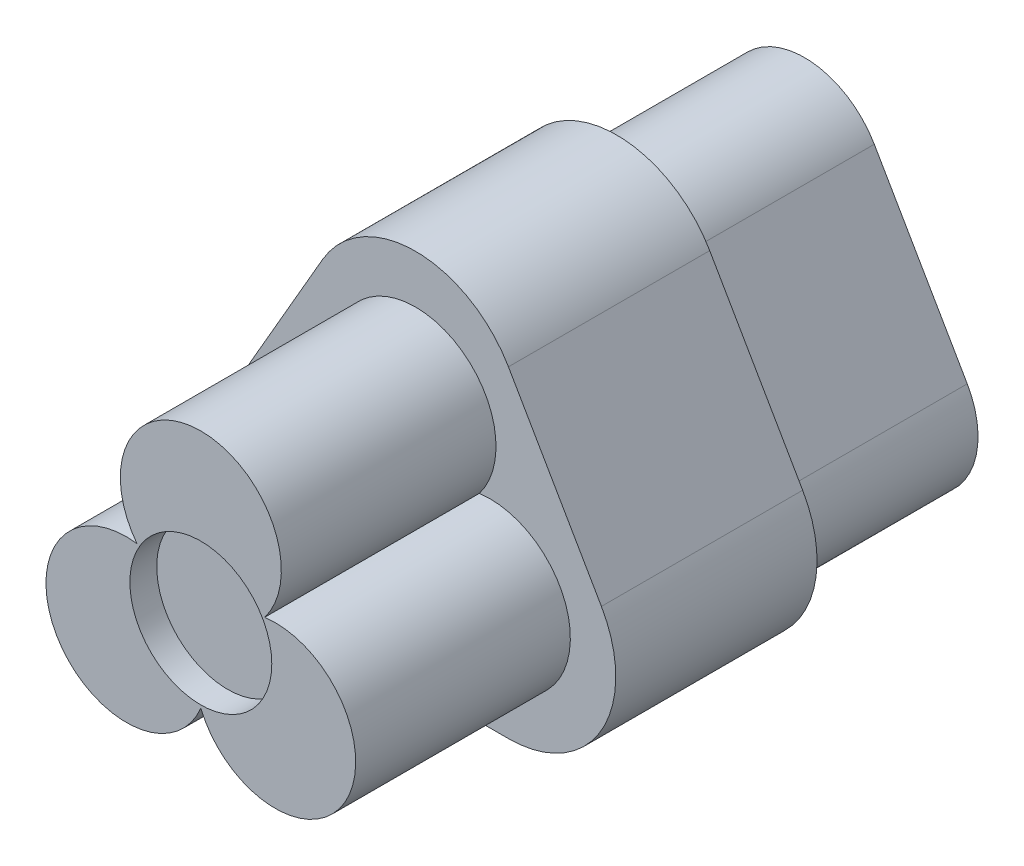
SolidWorks part; units mm, degrees
ref_plane "正面" through (0, 0, 0) normal (0, 0, 1) x (1, 0, 0)
ref_plane "平面" through (0, 0, 0) normal (0, 1, 0) x (1, 0, 0)
ref_plane "右側面" through (0, 0, 0) normal (1, 0, 0) x (0, 0, -1)
sketch "ｽｹｯﾁ1" plane through (0, 0, 0) normal (0, 0, 1) x (1, 0, 0)
  line L0 (0, 0) -> (0, 10) construction
  line L2 (-2.5981, 5.5) -> (-6.0622, -0.5)
  line L3 (-3.4641, -5) -> (3.4641, -5)
  line L4 (6.0622, -0.5) -> (2.5981, 5.5)
  arc A0 (3.4641, -5) -> (6.0622, -0.5) centre (3.4641, -2) ccw
  arc A1 (-6.0622, -0.5) -> (-3.4641, -5) centre (-3.4641, -2) ccw
  arc A2 (2.5981, 5.5) -> (-2.5981, 5.5) centre (0, 4) ccw
  point P3 (0, 6.6134)
  dimension "D2" = 3
  dimension "D1" = 5
extrude "ﾎﾞｽ - 押し出し1" add sketch "ｽｹｯﾁ1" along normal blind 7
sketch "ｽｹｯﾁ2" plane through (0, 0, 7) normal (0, 0, 1) x (1, 0, 0)
  line L6 (6.9282, 0) -> (3.4641, 6)
  line L7 (-3.4641, 6) -> (-6.9282, 0)
  line L8 (-3.4641, -6) -> (3.4641, -6)
  line L9 (6.9282, 0) -> (3.4641, 6)
  line L10 (-3.4641, 6) -> (-6.9282, 0)
  line L11 (-3.4641, -6) -> (3.4641, -6)
  arc A6 (3.4641, -6) -> (6.9282, 0) centre (3.4641, -2) ccw
  arc A7 (3.4641, 6) -> (-3.4641, 6) centre (0, 4) ccw
  arc A8 (-6.9282, 0) -> (-3.4641, -6) centre (-3.4641, -2) ccw
  arc A9 (3.4641, -6) -> (6.9282, 0) centre (3.4641, -2) ccw
  arc A10 (3.4641, 6) -> (-3.4641, 6) centre (0, 4) ccw
  arc A11 (-6.9282, 0) -> (-3.4641, -6) centre (-3.4641, -2) ccw
  dimension "D1" = 1
extrude "ﾎﾞｽ - 押し出し2" add sketch "ｽｹｯﾁ2" along normal blind 7.5
sketch "ｽｹｯﾁ3" plane through (0, 0, 14.5) normal (0, 0, 1) x (1, 0, 0)
  arc A3 (-2.3806, 1.3745) -> (0, -2.7489) centre (-2.7713, -1.6) ccw
  arc A5 (0, -2.7489) -> (2.3806, 1.3745) centre (2.7713, -1.6) ccw
  arc A7 (2.3806, 1.3745) -> (-2.3806, 1.3745) centre (0, 3.2) ccw
  point P6 (-2.7713, -1.6)
  point P15 (0, 3.2)
  point P16 (2.7713, -1.6)
  dimension "D5" = 6
  dimension "D6" = 6
extrude "ﾎﾞｽ - 押し出し3" add sketch "ｽｹｯﾁ3" along normal blind 8
sketch "ｽｹｯﾁ4" plane through (0, 0, 22.5) normal (0, 0, 1) x (1, 0, 0)
  circle A0 centre (0, 0) radius 2.6444
extrude "ｶｯﾄ - 押し出し1" cut sketch "ｽｹｯﾁ4" against normal blind 1
